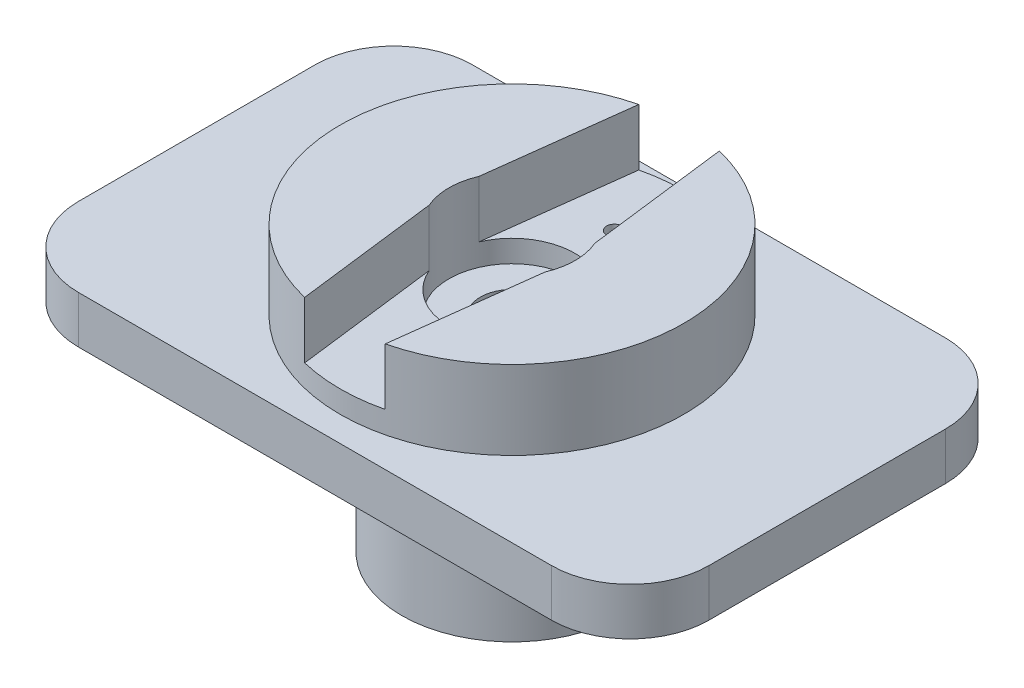
SolidWorks part; units mm, degrees
ref_plane "前视基准面" through (0, 0, 0) normal (0, 0, 1) x (1, 0, 0)
ref_plane "上视基准面" through (0, 0, 0) normal (0, 1, 0) x (1, 0, 0)
ref_plane "右视基准面" through (0, 0, 0) normal (1, 0, 0) x (0, 0, -1)
sketch "草图1" plane through (0, 0, 0) normal (0, 1, 0) x (1, 0, 0)
  line L1 (-20, 12.5) -> (20, 12.5)
  line L2 (-20, 12.5) -> (-20, -12.5)
  line L3 (-20, -12.5) -> (20, -12.5)
  line L4 (20, 12.5) -> (20, -12.5)
  line L5 (-20, 12.5) -> (20, -12.5) construction
  line L6 (-20, -12.5) -> (20, 12.5) construction
  point P0 (0, 0)
  dimension "D1" = 40
  dimension "D2" = 25
extrude "凸台-拉伸1" add sketch "草图1" along normal blind 3
sketch "草图2" plane through (0, 3, 0) normal (0, 1, 0) x (1, 0, 0)
  circle A0 centre (0, 0) radius 10.9
  dimension "D1" = 21.8
extrude "凸台-拉伸2" add sketch "草图2" along normal blind 5
sketch "草图3" plane through (0, 0, 0) normal (0, -1, 0) x (1, 0, 0)
  circle A0 centre (0, 0) radius 4
  dimension "D1" = 8
extrude "切除-拉伸1" cut sketch "草图3" against normal through all
sketch "草图4" plane through (0, 8, 0) normal (0, 1, 0) x (1, 0, 0)
  line L0 (3.6748, -1.5798) -> (2.3413, -12.3203)
  line L1 (0, -1000) -> (0, 49000) construction
  line L2 (-1000, 0) -> (49000, 0) construction
  line L3 (-3.6748, -1.5798) -> (-2.3413, -12.3203)
  line L4 (-3.6748, 1.5798) -> (-2.3413, 12.3203)
  line L5 (3.6748, 1.5798) -> (2.3413, 12.3203)
  line L6 (2.3413, -12.3203) -> (-2.3413, -12.3203)
  line L7 (2.3413, 12.3203) -> (-2.3413, 12.3203)
  line L8 (3.6748, -1.5798) -> (-3.6748, -1.5798)
  line L9 (3.6748, 1.5798) -> (-3.6748, 1.5798)
  circle A1 centre (0, 0) radius 4 construction
extrude "切除-拉伸2" cut sketch "草图4" against normal blind 3.6
sketch "草图5" plane through (0, 4.4, 0) normal (0, 1, 0) x (1, 0, 0)
  line L0 (-4.4, 0) -> (4.4, 0) construction
  circle A0 centre (0, -6.5) radius 0.5
  circle A1 centre (0, 6.5) radius 0.5
  dimension "D1" = 1
  dimension "D3" = 1
  dimension "D2" = 6.5
  dimension "D4" = 6.5
extrude "切除-拉伸3" cut sketch "草图5" against normal blind 4
fillet "圆角1" radius 5 1 edges at (20, 1.5, 12.5)
fillet "圆角2" radius 5 1 edges at (-20, 1.5, 12.5)
fillet "圆角3" radius 5 1 edges at (-20, 1.5, -12.5)
fillet "圆角4" radius 5 1 edges at (20, 1.5, -12.5)
sketch "草图6" plane through (0, 0, 0) normal (0, -1, 0) x (-1, 0, 0)
  circle A0 centre (0, 0) radius 7
  circle A1 centre (0, 0) radius 3
  dimension "D1" = 14
  dimension "D2" = 6
extrude "凸台-拉伸3" add sketch "草图6" along normal blind 10
sketch "草图7" plane through (0, 0, 0) normal (0, 1, 0) x (1, 0, 0)
  circle A0 centre (0, 0) radius 2
  circle A1 centre (0, 0) radius 4
  circle A2 centre (0, 0) radius 4
  dimension "D2" = 4
  dimension "D1" = 0
extrude "凸台-拉伸4" add sketch "草图7" along normal blind 3
